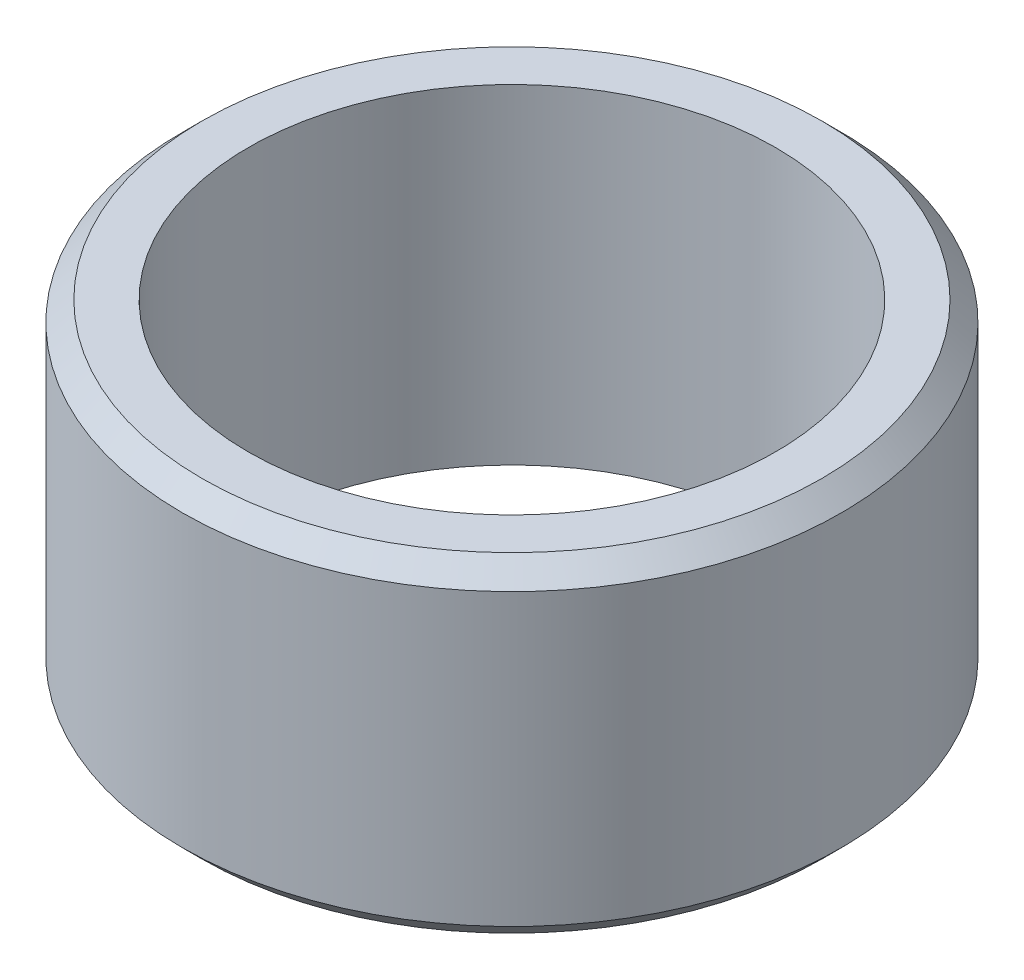
SolidWorks part; units mm, degrees
ref_plane "Front Plane" through (0, 0, 0) normal (0, 0, 1) x (1, 0, 0)
ref_plane "Top Plane" through (0, 0, 0) normal (0, 1, 0) x (1, 0, 0)
ref_plane "Right Plane" through (0, 0, 0) normal (1, 0, 0) x (0, 0, -1)
sketch "Sketch1" plane through (0, 0, 0) normal (0, 1, 0) x (1, 0, 0)
  circle A0 centre (0, 0) radius 4
  circle A1 centre (0, 0) radius 5
  dimension "D1" = 8
  dimension "D2" = 10
extrude "Boss-Extrude2" add sketch "Sketch1" along normal blind 5
chamfer "Chamfer1" distance 0.3 angle 45 2 edges at (0, 0, 5) (0, 5, 5)
